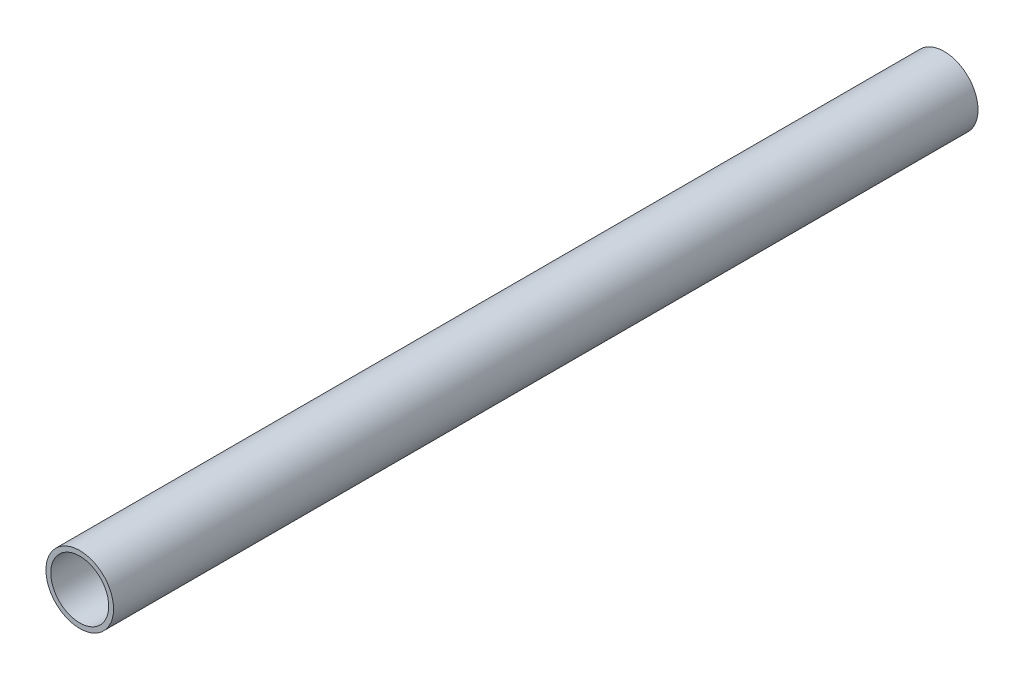
SolidWorks part; units mm, degrees
material "Thornel VCB-20 Carbon Cloth"
ref_plane "Front Plane" through (0, 0, 0) normal (0, 0, 1) x (1, 0, 0)
ref_plane "Top Plane" through (0, 0, 0) normal (0, 1, 0) x (1, 0, 0)
ref_plane "Right Plane" through (0, 0, 0) normal (1, 0, 0) x (0, 0, -1)
sketch "Sketch1" plane through (0, 0, 0) normal (0, 0, 1) x (1, 0, 0)
  circle A0 centre (0, 0) radius 9.525
  circle A1 centre (0, 0) radius 11.1125
  dimension "D1" = 19.05
  dimension "D2" = 22.225
extrude "Boss-Extrude1" add sketch "Sketch1" along normal mid plane 284.226
